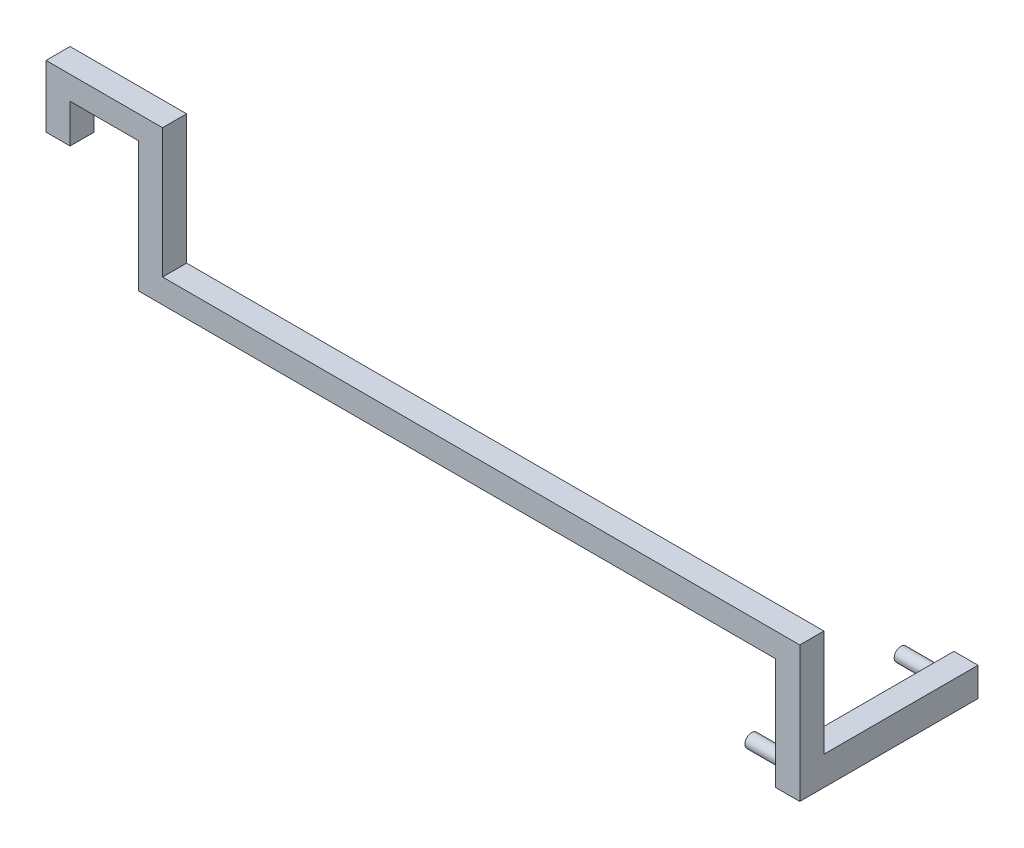
SolidWorks part; units mm, degrees
ref_plane "Front Plane" through (0, 0, 0) normal (0, 0, 1) x (1, 0, 0)
ref_plane "Top Plane" through (0, 0, 0) normal (0, 1, 0) x (1, 0, 0)
ref_plane "Right Plane" through (0, 0, 0) normal (1, 0, 0) x (0, 0, -1)
sketch "Sketch1" plane through (0, 0, 0) normal (0, 0, 1) x (1, 0, 0)
  line L0 (0, 6.7) -> (0, 8.05)
  line L5 (0, 0) -> (-5, 0)
  line L6 (-5, 0) -> (-5, 12.9)
  line L7 (-5, 12.9) -> (5.5, 12.9)
  line L8 (0, 8.05) -> (5.5, 8.05)
  line L10 (5.5, 12.9) -> (19.2, 12.9)
  line L11 (5.5, 8.05) -> (14.2, 8.05)
  line L13 (151.5, -13.95) -> (151.5, -42.1)
  line L14 (146.5, -18.95) -> (146.5, -42.1)
  line L15 (146.5, -42.1) -> (151.5, -42.1)
  line L16 (0, 6.7) -> (0, 0)
  line L17 (14.2, 8.05) -> (14.2, -18.95)
  line L18 (14.2, -18.95) -> (146.5, -18.95)
  line L19 (19.2, 12.9) -> (19.2, -13.95)
  line L21 (19.2, -13.95) -> (151.5, -13.95)
  dimension "D1" = 6.7
  dimension "D2" = 27
  dimension "D3" = 1.35
  dimension "D4" = 5
  dimension "D5" = 4.85
  dimension "D7" = 14.2
  dimension "D8" = 4.85
  dimension "D9" = 5
  dimension "D10" = 5
  dimension "D13" = 6.7
  dimension "D14" = 5
  dimension "D15" = 5
  dimension "D16" = 132.3
extrude "Boss-Extrude1" add sketch "Sketch1" along normal blind 5
sketch "Sketch5" plane through (0, 0, 0) normal (0, 0, -1) x (-1, 0, 0)
  line L0 (-146.5, -18.95) -> (-146.5, -42.1) construction
  line L1 (-151.5, -42.1) -> (-146.5, -42.1)
  line L2 (-151.5, -42.1) -> (-151.5, -36.1)
  line L3 (-151.5, -36.1) -> (-146.5, -36.1)
  line L4 (-146.5, -42.1) -> (-146.5, -36.1)
extrude "Boss-Extrude7" add sketch "Sketch5" along normal blind 32
sketch "Sketch4" plane through (146.5, 0, 0) normal (-1, 0, 0) x (0, 0, 1)
  line L0 (-32, -36.1) -> (0, -36.1) construction
  line L2 (-32, -42.1) -> (-32, -36.1) construction
  circle A2 centre (-29, -39.1) radius 1.4
  circle A3 centre (2, -39.1) radius 1.4
  dimension "D7" = 2.8
  dimension "D8" = 2.8
  dimension "D9" = 31
  dimension "D10" = 3
  dimension "D11" = 3
  dimension "D12" = 3
extrude "Boss-Extrude4" add sketch "Sketch4" along normal blind 8
